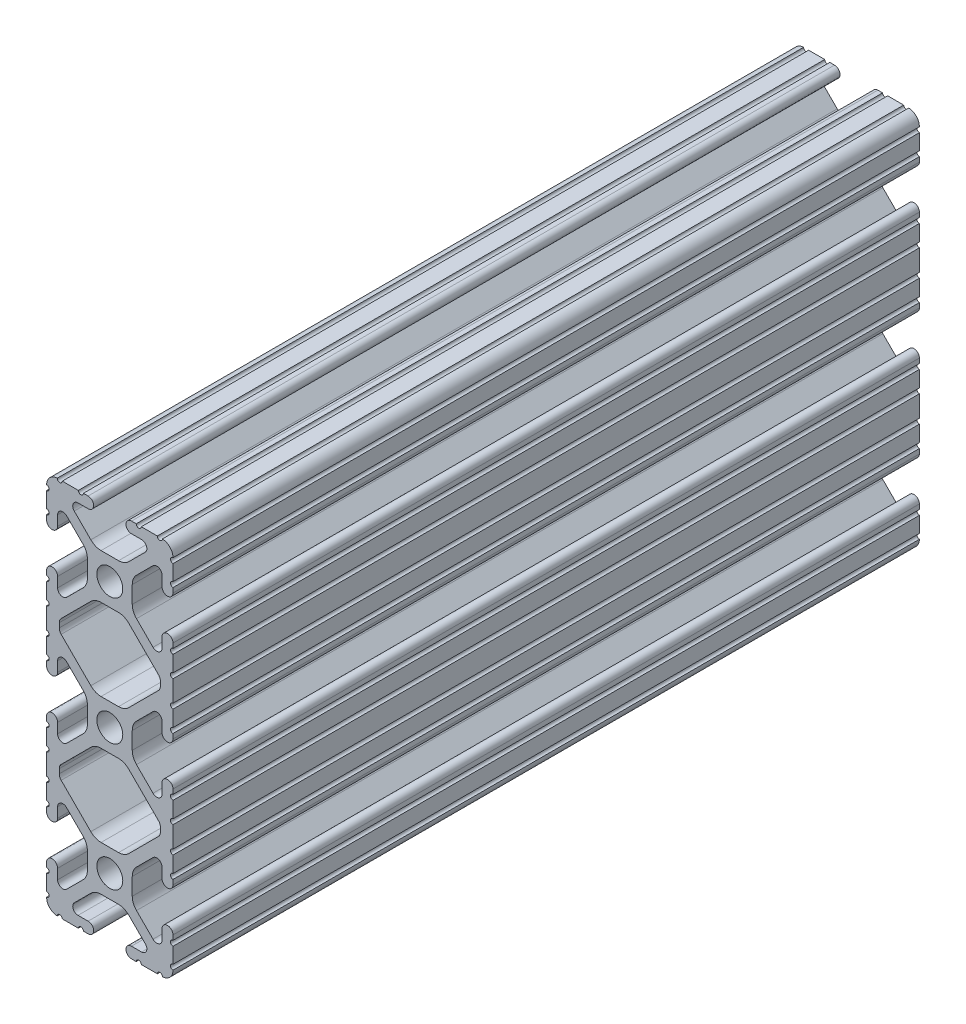
SolidWorks part; units mm, degrees
ref_plane "Front Plane" through (0, 0, 0) normal (0, 0, 1) x (1, 0, 0)
ref_plane "Top Plane" through (0, 0, 0) normal (0, 1, 0) x (1, 0, 0)
ref_plane "Right Plane" through (0, 0, 0) normal (1, 0, 0) x (0, 0, -1)
sketch "Sketch1" plane through (0, 0, 0) normal (0, 0, 1) x (1, 0, 0)
  line L0 (-12.7, 0) -> (12.7, 0) construction
  line L1 (-10.16, 13.1469) -> (-10.16, 12.2531)
  line L2 (-3.8143, 20.0397) -> (-9.7731, 14.0808)
  line L3 (0, 20.8915) -> (-1.7578, 20.8915)
  line L7 (-1.7578, 4.5085) -> (0, 4.5085)
  line L8 (-9.7731, 11.3192) -> (-3.8143, 5.3603)
  line L9 (-6.3246, 38.1) -> (-9.5504, 38.1)
  line L10 (-12.7, 34.8742) -> (-12.7, 31.7246)
  line L11 (-12.7, 30.7086) -> (-12.7, 29.7561)
  line L12 (-10.4902, 29.7561) -> (-10.4902, 31.7602)
  line L13 (-8.6864, 32.5073) -> (-5.3603, 29.1812)
  line L14 (-4.5085, 27.1248) -> (-4.5085, 23.6752)
  line L15 (-5.3603, 21.6188) -> (-8.6864, 18.2927)
  line L16 (-10.4902, 19.0398) -> (-10.4902, 21.0439)
  line L17 (-12.7, 21.0439) -> (-12.7, 20.0914)
  line L18 (-12.7, 19.0754) -> (-12.7, 15.8496)
  line L19 (-12.7, 14.8336) -> (-12.7, 10.5664)
  line L20 (-12.7, 9.5504) -> (-12.7, 6.3246)
  line L21 (-12.7, 5.3086) -> (-12.7, 4.3561)
  line L22 (-10.4902, 4.3561) -> (-10.4902, 6.3602)
  line L23 (-8.6864, 7.1073) -> (-5.3603, 3.7812)
  line L24 (-4.5085, 1.7248) -> (-4.5085, 0)
  line L25 (-11.5951, 28.6512) -> (-11.5951, 22.1488) construction
  line L26 (-11.5951, 25.4) -> (0, 25.4) construction
  line L27 (-12.7, 31.7246) -> (-6.3246, 38.1) construction
  line L28 (-12.7, 12.7) -> (0, 12.7) construction
  line L29 (-9.4336, 32.8168) -> (0, 32.8168) construction
  line L30 (-9.4336, 17.9832) -> (0, 17.9832) construction
  line L31 (-9.4336, 32.8168) -> (-9.4336, 17.9832) construction
  line L44 (0, 29.9085) -> (-1.7578, 29.9085)
  line L45 (-3.8143, 30.7603) -> (-7.1404, 34.0864)
  line L46 (-6.3932, 35.8902) -> (-4.3561, 35.8902)
  line L47 (-4.3561, 38.1) -> (-5.3086, 38.1)
  line L48 (0, 0) -> (0, 38.1) construction
  arc A0 (0, 28.0035) -> (0, 22.7965) centre (0, 25.4) ccw
  arc A1 (0, 2.6035) -> (-2.6035, 0) centre (0, 0) ccw
  arc A2 (-9.7731, 14.0808) -> (-10.16, 13.1469) centre (-8.8392, 13.1469) ccw
  arc A3 (-1.7578, 20.8915) -> (-3.8143, 20.0397) centre (-1.7578, 17.9832) ccw
  arc A8 (-3.8143, 5.3603) -> (-1.7578, 4.5085) centre (-1.7578, 7.4168) ccw
  arc A9 (-10.16, 12.2531) -> (-9.7731, 11.3192) centre (-8.8392, 12.2531) ccw
  arc A10 (-6.3246, 38.1) -> (-5.3086, 38.1) centre (-5.8166, 38.1) ccw
  arc A11 (-10.5664, 38.1) -> (-9.5504, 38.1) centre (-10.0584, 38.1) ccw
  arc A12 (-10.5664, 38.1) -> (-12.7, 35.8902) centre (-10.4888, 35.8902) ccw
  arc A13 (-12.7, 34.8742) -> (-12.7, 35.8902) centre (-12.7, 35.3822) ccw
  arc A14 (-12.7, 30.7086) -> (-12.7, 31.7246) centre (-12.7, 31.2166) ccw
  arc A15 (-12.7, 29.7561) -> (-10.4902, 29.7561) centre (-11.5951, 29.7561) ccw
  arc A16 (-8.6864, 32.5073) -> (-10.4902, 31.7602) centre (-9.4336, 31.7602) ccw
  arc A17 (-4.5085, 27.1248) -> (-5.3603, 29.1812) centre (-7.4168, 27.1248) ccw
  arc A18 (-5.3603, 21.6188) -> (-4.5085, 23.6752) centre (-7.4168, 23.6752) ccw
  arc A19 (-10.4902, 19.0398) -> (-8.6864, 18.2927) centre (-9.4336, 19.0398) ccw
  arc A20 (-10.4902, 21.0439) -> (-12.7, 21.0439) centre (-11.5951, 21.0439) ccw
  arc A21 (-12.7, 19.0754) -> (-12.7, 20.0914) centre (-12.7, 19.5834) ccw
  arc A22 (-12.7, 14.8336) -> (-12.7, 15.8496) centre (-12.7, 15.3416) ccw
  arc A23 (-12.7, 9.5504) -> (-12.7, 10.5664) centre (-12.7, 10.0584) ccw
  arc A24 (-12.7, 5.3086) -> (-12.7, 6.3246) centre (-12.7, 5.8166) ccw
  arc A25 (-12.7, 4.3561) -> (-10.4902, 4.3561) centre (-11.5951, 4.3561) ccw
  arc A26 (-8.6864, 7.1073) -> (-10.4902, 6.3602) centre (-9.4336, 6.3602) ccw
  arc A27 (-4.5085, 1.7248) -> (-5.3603, 3.7812) centre (-7.4168, 1.7248) ccw
  arc A49 (-3.8143, 30.7603) -> (-1.7578, 29.9085) centre (-1.7578, 32.8168) ccw
  arc A50 (-6.3932, 35.8902) -> (-7.1404, 34.0864) centre (-6.3932, 34.8336) ccw
  arc A51 (-4.3561, 35.8902) -> (-4.3561, 38.1) centre (-4.3561, 36.9951) ccw
  point P53 (-9.4336, 25.4)
  point P63 (-0.8789, 20.8915)
  dimension "D16" = 0.508
  dimension "D19" = 2.6035
  dimension "D27" = 1.0566
  dimension "D28" = 1.3208
  dimension "Rail Height" = 76.2
  dimension "Rail Width" = 25.4
  dimension "D3" = 2.2098
  dimension "D4" = 2.2098
  dimension "D5" = 2.2098
  dimension "D6" = 25.4
  dimension "D7" = 9.017
  dimension "D8" = 9.017
  dimension "TSlot Width" = 6.5024
  dimension "D9" = 2.2098
  dimension "D10" = 9.017
  dimension "D11" = 9.017
  dimension "D12" = 6.5024
  dimension "D13" = 6.5024
  dimension "D14" = 10.5664
  dimension "D15" = 5.3086
  dimension "D17" = 2.2098
  dimension "D18" = 16.383
  dimension "D2" = 45
  dimension "D20" = 45
  dimension "D21" = 45
  dimension "D22" = 2.54
  dimension "D23" = 25.4
  dimension "D24" = 4.2672
  dimension "D25" = 12.7508
  dimension "D26" = 14.8336
sketch "Sketch2" plane through (0, 0, 0) normal (1, 0, 0) x (0, 0, -1)
  line L0 (-1524, 0) -> (1524, 0)
  point P2 (-1460.5, 0)
  point P3 (1460.5, 0)
  dimension "Length" = 3048
  dimension "D1" = 63.5
  dimension "D2" = 63.5
sketch "Sketch3" plane through (0, 0, 0) normal (0, 0, 1) x (1, 0, 0)
  line L0 (-4.5085, 1.7248) -> (-4.5085, 0) construction
  line L1 (-8.6864, 7.1073) -> (-5.3603, 3.7812) construction
  line L2 (-10.4902, 4.3561) -> (-10.4902, 6.3602) construction
  line L3 (-12.7, 5.3086) -> (-12.7, 4.3561) construction
  line L4 (-12.7, 9.5504) -> (-12.7, 6.3246) construction
  line L5 (-12.7, 14.8336) -> (-12.7, 10.5664) construction
  line L6 (-12.7, 19.0754) -> (-12.7, 15.8496) construction
  line L7 (-12.7, 21.0439) -> (-12.7, 20.0914) construction
  line L8 (-10.4902, 19.0398) -> (-10.4902, 21.0439) construction
  line L9 (-5.3603, 21.6188) -> (-8.6864, 18.2927) construction
  line L10 (-4.5085, 27.1248) -> (-4.5085, 23.6752) construction
  line L11 (-8.6864, 32.5073) -> (-5.3603, 29.1812) construction
  line L12 (-10.4902, 29.7561) -> (-10.4902, 31.7602) construction
  line L13 (-12.7, 30.7086) -> (-12.7, 29.7561) construction
  line L14 (-12.7, 34.8742) -> (-12.7, 31.7246) construction
  line L15 (-6.3246, 38.1) -> (-9.5504, 38.1) construction
  line L16 (-4.3561, 38.1) -> (-5.3086, 38.1) construction
  line L17 (-6.3932, 35.8902) -> (-4.3561, 35.8902) construction
  line L18 (-3.8143, 30.7603) -> (-7.1404, 34.0864) construction
  line L19 (0, 29.9085) -> (-1.7578, 29.9085) construction
  line L20 (-1.7578, 4.5085) -> (0, 4.5085) construction
  line L21 (-9.7731, 11.3192) -> (-3.8143, 5.3603) construction
  line L22 (-10.16, 13.1469) -> (-10.16, 12.2531) construction
  line L23 (-3.8143, 20.0397) -> (-9.7731, 14.0808) construction
  line L24 (0, 20.8915) -> (-1.7578, 20.8915) construction
  line L25 (-4.5085, 1.7248) -> (-4.5085, 0)
  line L26 (-8.6864, 7.1073) -> (-5.3603, 3.7812)
  line L27 (-10.4902, 4.3561) -> (-10.4902, 6.3602)
  line L28 (-12.7, 5.3086) -> (-12.7, 4.3561)
  line L29 (-12.7, 9.5504) -> (-12.7, 6.3246)
  line L30 (-12.7, 14.8336) -> (-12.7, 10.5664)
  line L31 (-12.7, 19.0754) -> (-12.7, 15.8496)
  line L32 (-12.7, 21.0439) -> (-12.7, 20.0914)
  line L33 (-10.4902, 19.0398) -> (-10.4902, 21.0439)
  line L34 (-5.3603, 21.6188) -> (-8.6864, 18.2927)
  line L35 (-4.5085, 27.1248) -> (-4.5085, 23.6752)
  line L36 (-8.6864, 32.5073) -> (-5.3603, 29.1812)
  line L37 (-10.4902, 29.7561) -> (-10.4902, 31.7602)
  line L38 (-12.7, 30.7086) -> (-12.7, 29.7561)
  line L39 (-12.7, 34.8742) -> (-12.7, 31.7246)
  line L40 (-6.3246, 38.1) -> (-9.5504, 38.1)
  line L41 (-4.3561, 38.1) -> (-5.3086, 38.1)
  line L42 (-6.3932, 35.8902) -> (-4.3561, 35.8902)
  line L43 (-3.8143, 30.7603) -> (-7.1404, 34.0864)
  line L44 (0, 29.9085) -> (-1.7578, 29.9085)
  line L45 (-1.7578, 4.5085) -> (0, 4.5085)
  line L46 (-9.7731, 11.3192) -> (-3.8143, 5.3603)
  line L47 (-10.16, 13.1469) -> (-10.16, 12.2531)
  line L48 (-3.8143, 20.0397) -> (-9.7731, 14.0808)
  line L49 (0, 20.8915) -> (-1.7578, 20.8915)
  line L50 (0, 29.9085) -> (0, 28.0035)
  line L51 (0, 22.7965) -> (0, 20.8915)
  line L52 (0, 4.5085) -> (0, 2.6035)
  line L53 (-4.5085, 0) -> (-2.6035, 0)
  arc A0 (-4.5085, 1.7248) -> (-5.3603, 3.7812) centre (-7.4168, 1.7248) ccw construction
  arc A1 (-8.6864, 7.1073) -> (-10.4902, 6.3602) centre (-9.4336, 6.3602) ccw construction
  arc A2 (-12.7, 4.3561) -> (-10.4902, 4.3561) centre (-11.5951, 4.3561) ccw construction
  arc A3 (-12.7, 5.3086) -> (-12.7, 6.3246) centre (-12.7, 5.8166) ccw construction
  arc A4 (-12.7, 9.5504) -> (-12.7, 10.5664) centre (-12.7, 10.0584) ccw construction
  arc A5 (-12.7, 14.8336) -> (-12.7, 15.8496) centre (-12.7, 15.3416) ccw construction
  arc A6 (-12.7, 19.0754) -> (-12.7, 20.0914) centre (-12.7, 19.5834) ccw construction
  arc A7 (-10.4902, 21.0439) -> (-12.7, 21.0439) centre (-11.5951, 21.0439) ccw construction
  arc A8 (-10.4902, 19.0398) -> (-8.6864, 18.2927) centre (-9.4336, 19.0398) ccw construction
  arc A9 (-5.3603, 21.6188) -> (-4.5085, 23.6752) centre (-7.4168, 23.6752) ccw construction
  arc A10 (-4.5085, 27.1248) -> (-5.3603, 29.1812) centre (-7.4168, 27.1248) ccw construction
  arc A11 (-8.6864, 32.5073) -> (-10.4902, 31.7602) centre (-9.4336, 31.7602) ccw construction
  arc A12 (-12.7, 29.7561) -> (-10.4902, 29.7561) centre (-11.5951, 29.7561) ccw construction
  arc A13 (-12.7, 30.7086) -> (-12.7, 31.7246) centre (-12.7, 31.2166) ccw construction
  arc A14 (-12.7, 34.8742) -> (-12.7, 35.8902) centre (-12.7, 35.3822) ccw construction
  arc A15 (-10.5664, 38.1) -> (-12.7, 35.8902) centre (-10.4888, 35.8902) ccw construction
  arc A16 (-10.5664, 38.1) -> (-9.5504, 38.1) centre (-10.0584, 38.1) ccw construction
  arc A17 (-6.3246, 38.1) -> (-5.3086, 38.1) centre (-5.8166, 38.1) ccw construction
  arc A18 (-4.3561, 35.8902) -> (-4.3561, 38.1) centre (-4.3561, 36.9951) ccw construction
  arc A19 (-6.3932, 35.8902) -> (-7.1404, 34.0864) centre (-6.3932, 34.8336) ccw construction
  arc A20 (-3.8143, 30.7603) -> (-1.7578, 29.9085) centre (-1.7578, 32.8168) ccw construction
  arc A21 (-3.8143, 5.3603) -> (-1.7578, 4.5085) centre (-1.7578, 7.4168) ccw construction
  arc A22 (-10.16, 12.2531) -> (-9.7731, 11.3192) centre (-8.8392, 12.2531) ccw construction
  arc A23 (-9.7731, 14.0808) -> (-10.16, 13.1469) centre (-8.8392, 13.1469) ccw construction
  arc A24 (-1.7578, 20.8915) -> (-3.8143, 20.0397) centre (-1.7578, 17.9832) ccw construction
  arc A25 (0, 2.6035) -> (-2.6035, 0) centre (0, 0) ccw construction
  arc A26 (0, 28.0035) -> (0, 22.7965) centre (0, 25.4) ccw construction
  arc A27 (-4.5085, 1.7248) -> (-5.3603, 3.7812) centre (-7.4168, 1.7248) ccw
  arc A28 (-8.6864, 7.1073) -> (-10.4902, 6.3602) centre (-9.4336, 6.3602) ccw
  arc A29 (-12.7, 4.3561) -> (-10.4902, 4.3561) centre (-11.5951, 4.3561) ccw
  arc A30 (-12.7, 5.3086) -> (-12.7, 6.3246) centre (-12.7, 5.8166) ccw
  arc A31 (-12.7, 9.5504) -> (-12.7, 10.5664) centre (-12.7, 10.0584) ccw
  arc A32 (-12.7, 14.8336) -> (-12.7, 15.8496) centre (-12.7, 15.3416) ccw
  arc A33 (-12.7, 19.0754) -> (-12.7, 20.0914) centre (-12.7, 19.5834) ccw
  arc A34 (-10.4902, 21.0439) -> (-12.7, 21.0439) centre (-11.5951, 21.0439) ccw
  arc A35 (-10.4902, 19.0398) -> (-8.6864, 18.2927) centre (-9.4336, 19.0398) ccw
  arc A36 (-5.3603, 21.6188) -> (-4.5085, 23.6752) centre (-7.4168, 23.6752) ccw
  arc A37 (-4.5085, 27.1248) -> (-5.3603, 29.1812) centre (-7.4168, 27.1248) ccw
  arc A38 (-8.6864, 32.5073) -> (-10.4902, 31.7602) centre (-9.4336, 31.7602) ccw
  arc A39 (-12.7, 29.7561) -> (-10.4902, 29.7561) centre (-11.5951, 29.7561) ccw
  arc A40 (-12.7, 30.7086) -> (-12.7, 31.7246) centre (-12.7, 31.2166) ccw
  arc A41 (-12.7, 34.8742) -> (-12.7, 35.8902) centre (-12.7, 35.3822) ccw
  arc A42 (-10.5664, 38.1) -> (-12.7, 35.8902) centre (-10.4888, 35.8902) ccw
  arc A43 (-10.5664, 38.1) -> (-9.5504, 38.1) centre (-10.0584, 38.1) ccw
  arc A44 (-6.3246, 38.1) -> (-5.3086, 38.1) centre (-5.8166, 38.1) ccw
  arc A45 (-4.3561, 35.8902) -> (-4.3561, 38.1) centre (-4.3561, 36.9951) ccw
  arc A46 (-6.3932, 35.8902) -> (-7.1404, 34.0864) centre (-6.3932, 34.8336) ccw
  arc A47 (-3.8143, 30.7603) -> (-1.7578, 29.9085) centre (-1.7578, 32.8168) ccw
  arc A48 (-3.8143, 5.3603) -> (-1.7578, 4.5085) centre (-1.7578, 7.4168) ccw
  arc A49 (-10.16, 12.2531) -> (-9.7731, 11.3192) centre (-8.8392, 12.2531) ccw
  arc A50 (-9.7731, 14.0808) -> (-10.16, 13.1469) centre (-8.8392, 13.1469) ccw
  arc A51 (-1.7578, 20.8915) -> (-3.8143, 20.0397) centre (-1.7578, 17.9832) ccw
  arc A52 (0, 2.6035) -> (-2.6035, 0) centre (0, 0) ccw
  arc A53 (0, 28.0035) -> (0, 22.7965) centre (0, 25.4) ccw
extrude "Boss-Extrude1" add sketch "Sketch3" along normal mid plane 149.9997
mirror "Mirror1" about plane through (0, 0, 0) normal (1, 0, 0) of bodies 104
mirror "Mirror2" about plane through (0, 0, 0) normal (0, 1, 0) of bodies 105
equation "\"D3@Sketch1\" = \"Rail Width@Sketch1\" * 0.0870in"
equation "\"D4@Sketch1\"=\"D3@Sketch1\""
equation "\"D5@Sketch1\"=\"D3@Sketch1\""
equation "\"D6@Sketch1\" = \"Rail Width@Sketch1\""
equation "\"D7@Sketch1\" = \"Rail Width@Sketch1\" * 0.3550in"
equation "\"D8@Sketch1\"=\"D7@Sketch1\""
equation "\"D9@Sketch1\"=\"D4@Sketch1\""
equation "\"D10@Sketch1\"=\"D8@Sketch1\""
equation "\"D11@Sketch1\"=\"D7@Sketch1\""
equation "\"D12@Sketch1\"=\"TSlot Width@Sketch1\""
equation "\"D14@Sketch1\" = \"Rail Width@Sketch1\" * 0.4160in"
equation "\"D15@Sketch1\" = \"Rail Width@Sketch1\" * 0.2090in"
equation "\"D16@Sketch1\" = \"Rail Width@Sketch1\" * 0.0200in"
equation "\"D17@Sketch1\"=\"D9@Sketch1\""
equation "\"D18@Sketch1\" = \"Rail Width@Sketch1\" * 0.6450in"
equation "\"D19@Sketch1\" = \"Rail Width@Sketch1\" * 0.1025in"
equation "\"D22@Sketch1\"=\"Rail Width@Sketch1\"*0.10"
equation "\"D23@Sketch1\"=\"Rail Width@Sketch1\""
equation "\"D24@Sketch1\"=\"Rail Width@Sketch1\"*0.1680in"
equation "\"D25@Sketch1\"=\"Rail Width@Sketch1\"*0.5020in"
equation "\"D26@Sketch1\"=\"Rail Width@Sketch1\"*0.584"
equation "\"D27@Sketch1\"=\"Rail Width@Sketch1\"*0.0416in"
equation "\"D28@Sketch1\"=\"Rail Width@Sketch1\"*0.052"
equation "\"D1@Boss-Extrude1\" = \"Length@Sketch2\""
equation "\"D2@Sketch2\"=\"D1@Sketch2\""
equation "\"D13@Sketch1\"=\"TSlot Width@Sketch1\""
